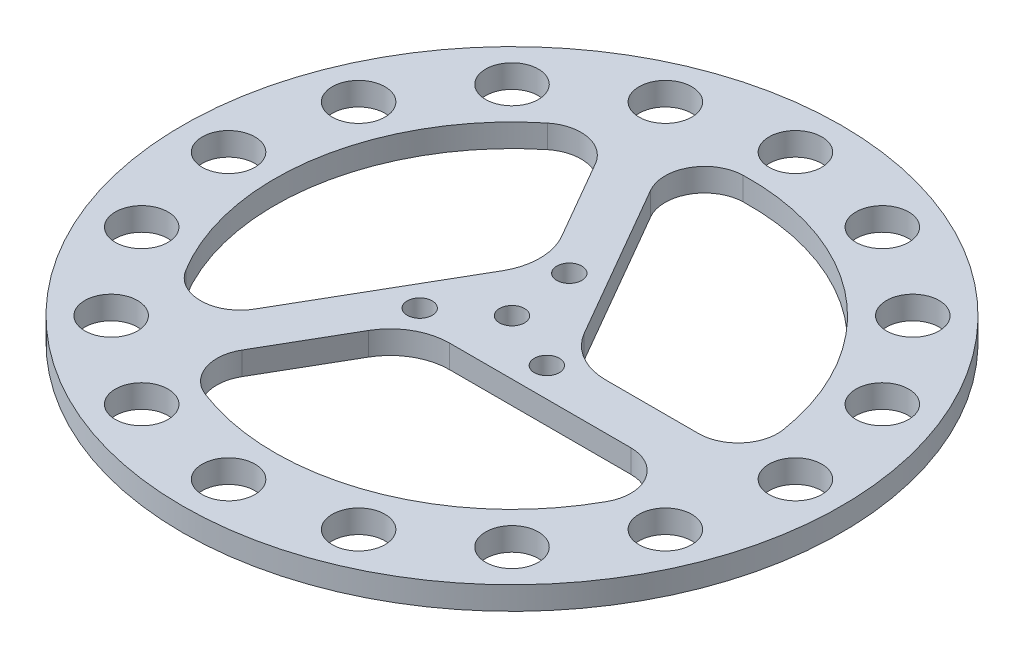
SolidWorks part; units mm, degrees
ref_plane "Front Plane" through (0, 0, 0) normal (0, 0, 1) x (1, 0, 0)
ref_plane "Top Plane" through (0, 0, 0) normal (0, 1, 0) x (1, 0, 0)
ref_plane "Right Plane" through (0, 0, 0) normal (1, 0, 0) x (0, 0, -1)
sketch "Sketch1" plane through (0, 0, 0) normal (0, 1, 0) x (1, 0, 0)
  circle A0 centre (0, 0) radius 50
  circle A1 centre (0, 0) radius 1.9
  dimension "D1" = 100
  dimension "D2" = 3.8
extrude "Boss-Extrude1" add sketch "Sketch1" along normal blind 3.5
sketch "Sketch2" plane through (0, 3.5, 0) normal (0, 1, 0) x (1, 0, 0)
  circle A0 centre (0, 0) radius 43 construction
  circle A1 centre (0, 43) radius 4
  circle A2 centre (0, 0) radius 50 construction
  dimension "D1" = 8
  dimension "D2" = 7
extrude "Cut-Extrude1" cut sketch "Sketch2" against normal up to surface (3.5 mm away) up to face at (0, 0, 50)
pattern_circular "CirPattern1" count 16 over 360 about axis through (0, 0, 0) along (0, 1, 0) of "Cut-Extrude1"
sketch "Sketch3" plane through (0, 3.5, 0) normal (0, 1, 0) x (1, 0, 0)
  line L0 (2.3094, -1.3333) -> (35.9753, -1.3333)
  line L19 (0, 16.6667) -> (-14.4338, -8.3333)
  line L20 (-14.4338, -8.3333) -> (14.4338, -8.3333)
  line L21 (14.4338, -8.3333) -> (0, 16.6667)
  line L22 (0, 2.6667) -> (-2.3094, -1.3333)
  line L23 (-2.3094, -1.3333) -> (2.3094, -1.3333)
  line L24 (2.3094, -1.3333) -> (0, 2.6667)
  line L25 (0, 16.6667) -> (-10.2942, 34.4968)
  circle A2 centre (0, 0) radius 8.3333 construction
  circle A3 centre (0, 0) radius 1.3333 construction
  circle A4 centre (0, 0) radius 36
  circle A6 centre (0, 0) radius 50 construction
  arc A9 (7.7942, 3.1667) -> (15.5885, -1.3333) centre (15.5885, 7.6667) ccw
  arc A10 (29.6348, -1.3333) -> (35.5618, 5.6) centre (29.6348, 4.6667) ccw
  arc A11 (-0.917, 35.9883) -> (-5.9603, 26.9903) centre (-0.7642, 29.9903) ccw
  point P1 (0, -8.3333)
  dimension "D1" = 14
  dimension "D4" = 6
  dimension "D5" = 9
  dimension "D2" = 25
  dimension "D3" = 7
extrude "Cut-Extrude5" cut sketch "Sketch3" against normal blind 10
pattern_circular "CirPattern3" count 3 over 360 about axis through (0, 0, 0) along (0, 1, 0) of "Cut-Extrude5"
sketch "Sketch4" plane through (0, 0, 0) normal (0, 1, 0) x (1, 0, 0)
  line L0 (-10.1511, 20.2489) -> (-4.0889, 23.7489) construction
  line L4 (-6.6395, 14.1667) -> (-13.6627, 26.3312) construction
  line L5 (7.7942, 3.1667) -> (-5.9603, 26.9903) construction
  line L6 (-7.12, 21.9989) -> (1.0945, 5.1567) construction
  circle A0 centre (0, 0) radius 10 construction
  circle A1 centre (-1.2307, 9.924) radius 1.9
  circle A2 centre (9.1831, -3.8992) radius 1.9
  circle A3 centre (-7.995, -6.0062) radius 1.9
  point P12 (-1.2307, 9.924)
  point P22 (-0.0142, 0.0062)
  dimension "D1" = 3.8
  dimension "D3" = 10
  dimension "D4" = 86
  dimension "D2" = 3
extrude "Cut-Extrude6" cut sketch "Sketch4" along normal up to surface (3.5 mm away) up to face at (-17.9756, 3.5, -6.1448)
